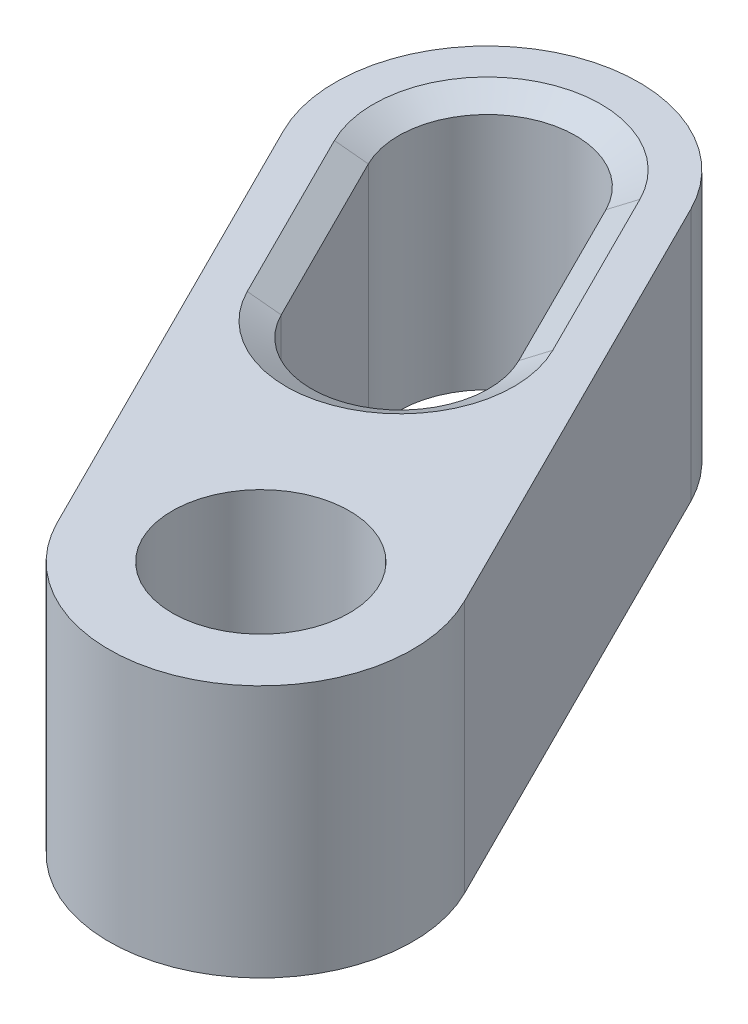
SolidWorks part; units mm, degrees
ref_plane "Front Plane" through (0, 0, 0) normal (0, 0, 1) x (1, 0, 0)
ref_plane "Top Plane" through (0, 0, 0) normal (0, 1, 0) x (1, 0, 0)
ref_plane "Right Plane" through (0, 0, 0) normal (1, 0, 0) x (0, 0, -1)
sketch "Sketch1" plane through (0, 0, 0) normal (0, 1, 0) x (1, 0, 0)
  line L0 (5.9774, 29.7) -> (20.7071, 29.7) construction
  line L1 (0, 0) -> (20, 0) construction
  line L2 (0, 0) -> (0, 20) construction
  line L3 (0, 20) -> (20, 20) construction
  line L4 (20, 0) -> (20, 20) construction
  line L5 (-6, 20) -> (26, 20) construction
  line L6 (-6, 20) -> (-6, 39.7) construction
  line L7 (-6, 39.7) -> (26, 39.7) construction
  line L8 (26, 20) -> (26, 39.7) construction
  line L9 (12.75, 34.2) -> (10, 39.7) construction
  line L10 (15.4333, 35.5416) -> (10.9611, 44.4859)
  line L11 (10.0667, 32.8584) -> (5.5946, 41.8026)
  line L12 (11.5652, 40.4826) -> (9.8431, 43.9269)
  line L13 (8.4348, 38.9174) -> (6.7126, 42.3616)
  arc A0 (8.4348, 38.9174) -> (11.5652, 40.4826) centre (10, 39.7) ccw
  circle A1 centre (12.75, 34.2) radius 1.75
  arc A2 (10.0667, 32.8584) -> (15.4333, 35.5416) centre (12.75, 34.2) ccw
  arc A4 (9.8431, 43.9269) -> (6.7126, 42.3616) centre (8.2779, 43.1443) ccw
  arc A5 (10.9611, 44.4859) -> (5.5946, 41.8026) centre (8.2779, 43.1443) ccw
  dimension "D6" = 3.5
  dimension "D7" = 3.5
  dimension "D10" = 6
  dimension "D11" = 10
  dimension "D1" = 20
  dimension "D2" = 20
  dimension "D3" = 19.7
  dimension "D4" = 32
  dimension "D5" = 6
  dimension "D8" = 12.75
  dimension "D9" = 14.2
  dimension "D13" = 10
extrude "Boss-Extrude1" add sketch "Sketch1" along normal blind 5
chamfer "Chamfer1" distance 0.5 angle 30 4 edges at (10.7826, 5, -38.1348) (10.7042, 5, -42.2048) (7.5737, 5, -40.6395) (7.4952, 5, -44.7095)
